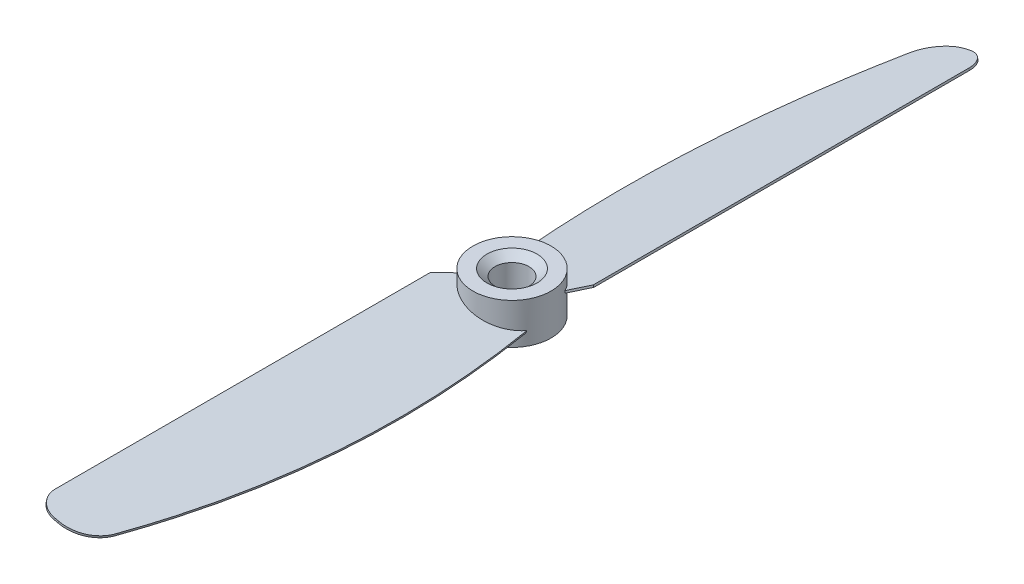
SolidWorks part; units mm, degrees
ref_plane "Front Plane" through (0, 0, 0) normal (0, 0, 1) x (1, 0, 0)
ref_plane "Top Plane" through (0, 0, 0) normal (0, 1, 0) x (1, 0, 0)
ref_plane "Right Plane" through (0, 0, 0) normal (1, 0, 0) x (0, 0, -1)
sketch "Sketch1" plane through (0, 0, 0) normal (0, 1, 0) x (1, 0, 0)
  circle A0 centre (0, 0) radius 5.75
  dimension "D1" = 11.5
extrude "Boss-Extrude1" add sketch "Sketch1" along normal mid plane 6
sketch "Sketch2" plane through (0, 0, 0) normal (0, 0, 1) x (1, 0, 0)
  line L0 (-5.75, 1.3275) -> (5.75, -1.3275) construction
  line L1 (-5.75, 3) -> (-5.75, -3) construction
  line L2 (5.75, -3) -> (5.75, 3) construction
  line L3 (-5.75, -3) -> (5.75, -3) construction
  dimension "D1" = 13
ref_plane "Plane2" through (0, 0, 0) normal (-0.225, -0.9744, 0) x (0.9744, -0.225, 0)
sketch "Sketch3" plane through (0, 0, 0) normal (-0.225, -0.9744, 0) x (0.9744, -0.225, 0)
  line L0 (-4.5943, 1.9541) -> (-7.005, 5.194)
  line L1 (-7.005, 5.194) -> (-7.005, 60.5)
  line L2 (-4.005, 63.5) -> (-3.3491, 63.5)
  arc A0 (1.5446, 59.5254) -> (-3.3491, 63.5) centre (-3.3491, 58.5) ccw
  arc A1 (-7.005, 60.5) -> (-4.005, 63.5) centre (-4.005, 60.5) cw
  ellipse E0 centre (0.6749, 0) end of major axis (0.6749, 5.75) minor radius 5.6026 construction
  ellipse E1 centre (-0.6749, 0) end of major axis (-0.6749, 5.75) minor radius 5.6026 construction
  spline S0 degree 2 poles (-4.5943, 1.9541) (0.4696, 8.86) (4.8343, 1.046) knots 0 0 0 1 1 1
  spline S1 degree 2 poles (1.5446, 59.5254) (9.4752, 30.694) (4.8343, 1.046) knots 0 0 0 1 1 1
  dimension "D2" = 5
  dimension "D3" = 3
  dimension "D1" = 63.5
extrude "Boss-Extrude2" add sketch "Sketch3" along normal mid plane 0.3
pattern_circular "CirPattern1" count 2 over 360 about axis through (0, 3, 0) along (0, -1, 0) of "Boss-Extrude2"
sketch "Sketch4" plane through (0, -3, 0) normal (0, -1, 0) x (1, 0, 0)
  circle A0 centre (0, 0) radius 2.5
  dimension "D1" = 5
extrude "Cut-Extrude1" cut sketch "Sketch4" against normal through all
chamfer "Chamfer2" distance 1 angle 50 2 edges at (0, -3, -2.5) (0, 3, -2.5)
